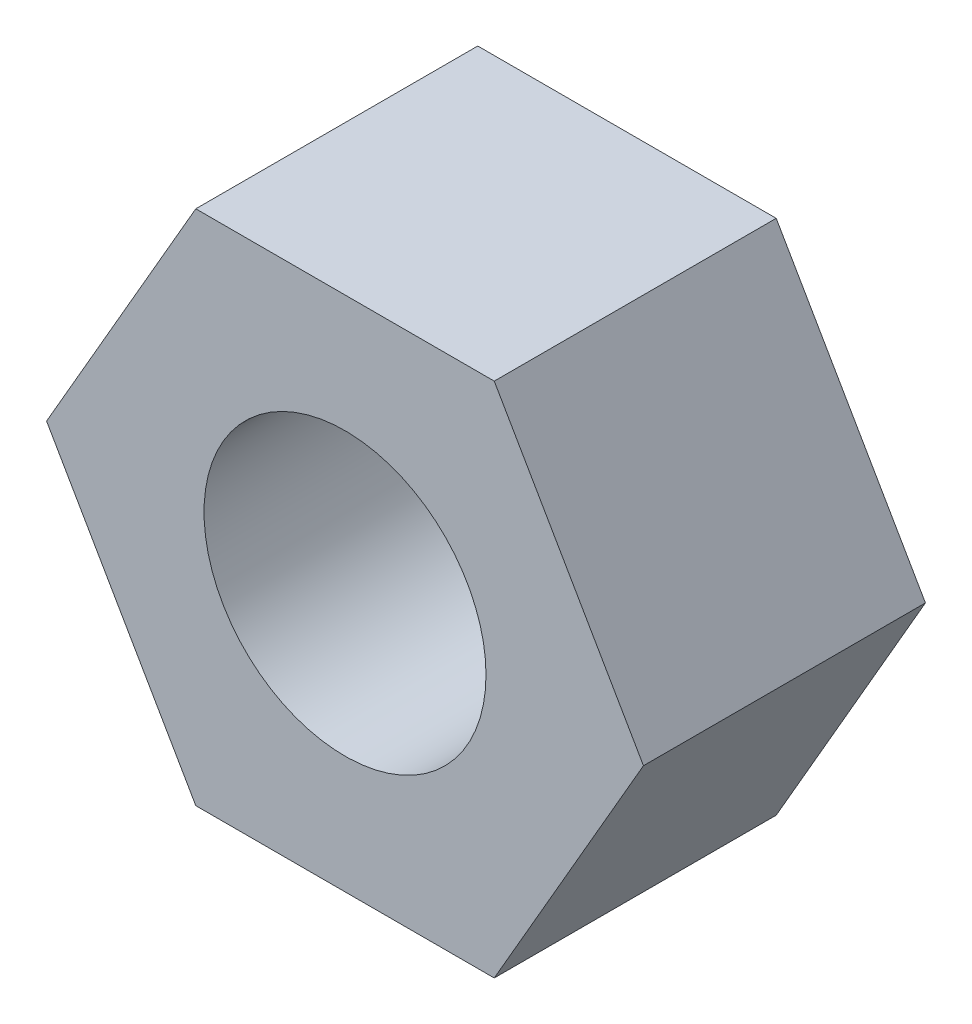
SolidWorks part; units mm, degrees
ref_plane "Front Plane" through (0, 0, 0) normal (0, 0, 1) x (1, 0, 0)
ref_plane "Top Plane" through (0, 0, 0) normal (0, 1, 0) x (1, 0, 0)
ref_plane "Right Plane" through (0, 0, 0) normal (1, 0, 0) x (0, 0, -1)
sketch "Sketch1" plane through (0, 0, 0) normal (0, 0, 1) x (1, 0, 0)
  line L1 (-9.3246, -45.6639) -> (-10.9123, -42.9139)
  line L2 (-10.9123, -42.9139) -> (-14.0877, -42.9139)
  line L3 (-14.0877, -42.9139) -> (-15.6754, -45.6639)
  line L4 (-15.6754, -45.6639) -> (-14.0877, -48.4139)
  line L5 (-14.0877, -48.4139) -> (-10.9123, -48.4139)
  line L6 (-10.9123, -48.4139) -> (-9.3246, -45.6639)
  circle A1 centre (-12.5, -45.6639) radius 1.5
  circle A2 centre (-12.5, -45.6639) radius 2.75 construction
  dimension "D1" = 5.5
extrude "Boss-Extrude1" add sketch "Sketch1" along normal blind 3
